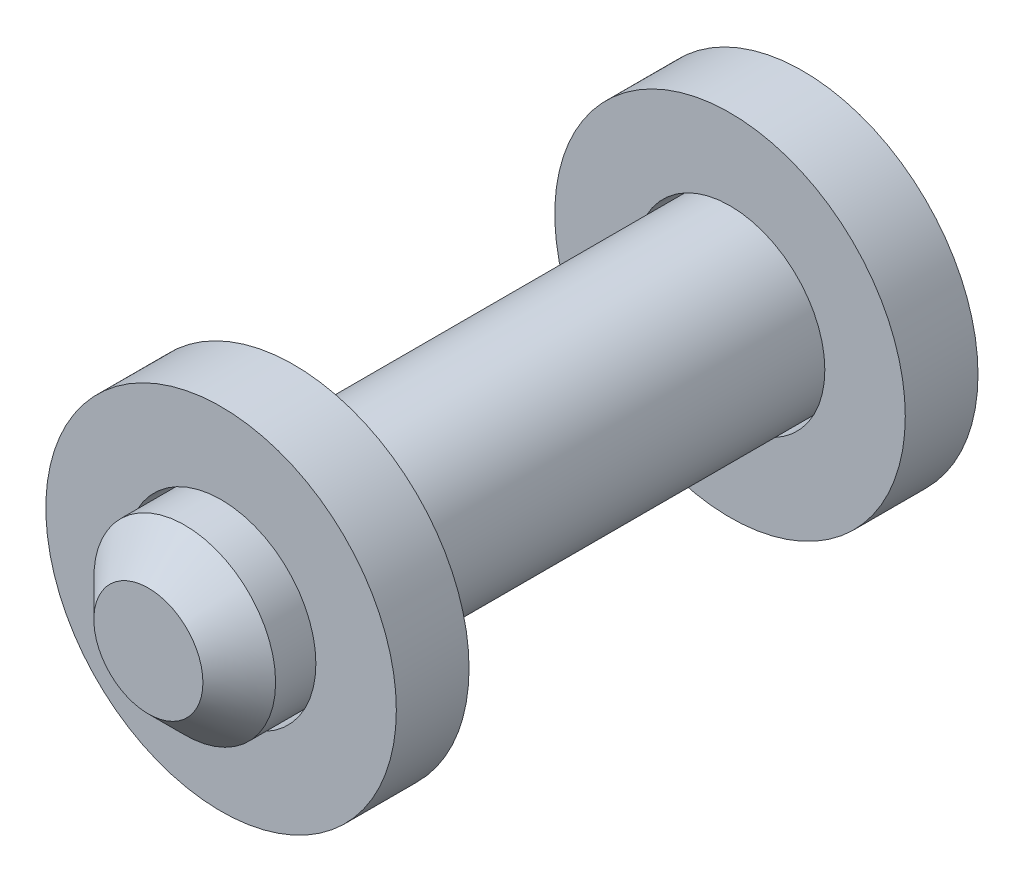
SolidWorks part; units mm, degrees
ref_plane "Front Plane" through (0, 0, 0) normal (0, 0, 1) x (1, 0, 0)
ref_plane "Top Plane" through (0, 0, 0) normal (0, 1, 0) x (1, 0, 0)
ref_plane "Right Plane" through (0, 0, 0) normal (1, 0, 0) x (0, 0, -1)
sketch "Sketch1" plane through (0, 0, 0) normal (0, 0, 1) x (1, 0, 0)
  circle A0 centre (0, 0) radius 2.5
  dimension "D1" = 5
extrude "Boss-Extrude1" add sketch "Sketch1" along normal mid plane 20
chamfer "Chamfer1" distance 1 angle 45 2 edges at (2.5, 0, -10) (2.5, 0, 10)
ref_plane "Plane1" through (0, 0, 6) normal (0, 0, 1) x (1, 0, 0)
sketch "Sketch2" plane through (0, 0, 6) normal (0, 0, 1) x (1, 0, 0)
  circle A0 centre (0, 0) radius 2.6077
  circle A1 centre (0, 0) radius 4.8208
extrude "Boss-Extrude2" add sketch "Sketch2" along normal blind 2 separate body
mirror "Mirror2" about plane through (0, 0, 0) normal (0, 0, 1) of bodies 102
